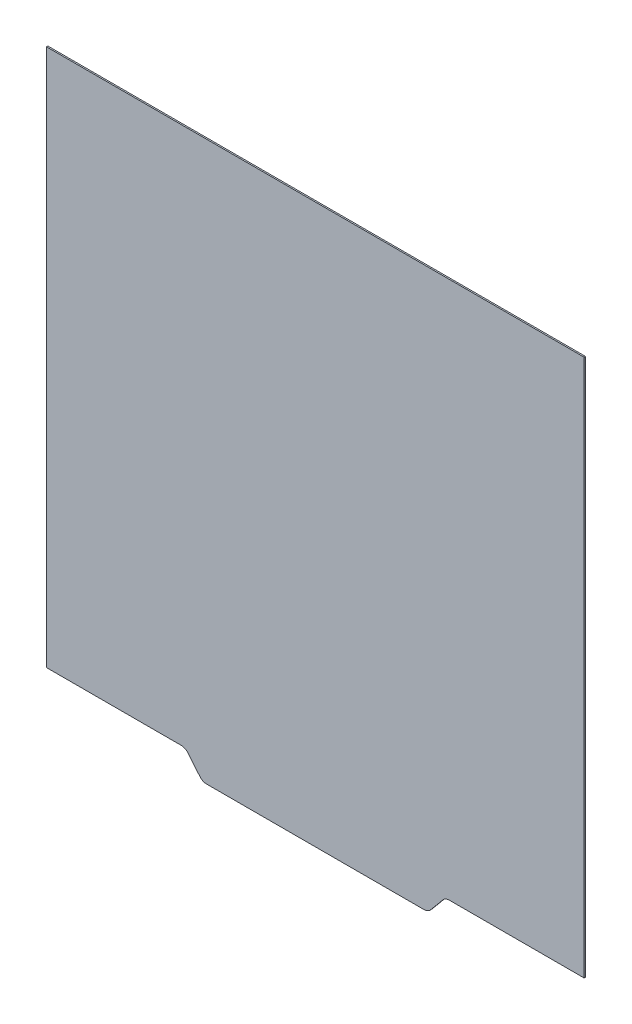
SolidWorks part; units mm, degrees
ref_plane "前视基准面" through (0, 0, 0) normal (0, 0, 1) x (1, 0, 0)
ref_plane "上视基准面" through (0, 0, 0) normal (0, 1, 0) x (1, 0, 0)
ref_plane "右视基准面" through (0, 0, 0) normal (1, 0, 0) x (0, 0, -1)
sketch "草图1" plane through (0, 0, 0) normal (0, 0, 1) x (1, 0, 0)
  line L0 (-99.0878, -159.5383) -> (-99.0878, -171.5383)
  line L1 (-179.0878, -159.5383) -> (130.9122, -159.5383)
  line L2 (-179.0878, -159.5383) -> (-179.0878, 150.4617)
  line L3 (-179.0878, 150.4617) -> (130.9122, 150.4617)
  line L4 (130.9122, -159.5383) -> (130.9122, 150.4617)
  line L5 (-179.0878, -159.5383) -> (130.9122, 150.4617) construction
  line L6 (-179.0878, 150.4617) -> (130.9122, -159.5383) construction
  line L7 (-99.0878, -171.5383) -> (50.9122, -171.5383)
  line L8 (50.9122, -171.5383) -> (50.9122, -159.5383)
  point P0 (-24.0878, -4.5383)
  dimension "D1" = 310
  dimension "D2" = 310
  dimension "D3" = 150
  dimension "D4" = 12
  dimension "D5" = 80
extrude "凸台-拉伸1" add sketch "草图1" along normal blind 0.8 contours L1 L4 L3 L2 | L7 L8 L1 L0
sketch "草图2" plane through (0, 0, 0) normal (0, 0, -1) x (-1, 0, 0)
  line L0 (99.0878, -159.5383) -> (89.0878, -171.5383)
  line L1 (99.0878, -171.5383) -> (-50.9122, -171.5383) construction
  line L2 (89.0878, -171.5383) -> (99.0878, -171.5383)
  line L3 (99.0878, -171.5383) -> (99.0878, -159.5383)
  line L4 (-50.9122, -159.5383) -> (-40.9122, -171.5383)
  line L5 (-40.9122, -171.5383) -> (-50.9122, -171.5383)
  line L6 (-50.9122, -171.5383) -> (-50.9122, -159.5383)
  dimension "D1" = 10
  dimension "D2" = 10
extrude "切除-拉伸1" cut sketch "草图2" against normal blind 0.8
fillet "圆角1" radius 5 4 edges at (-99.0878, -159.5383, 0.4) (-89.0878, -171.5383, 0.4) (50.9122, -159.5383, 0.4) (40.9122, -171.5383, 0.4)
